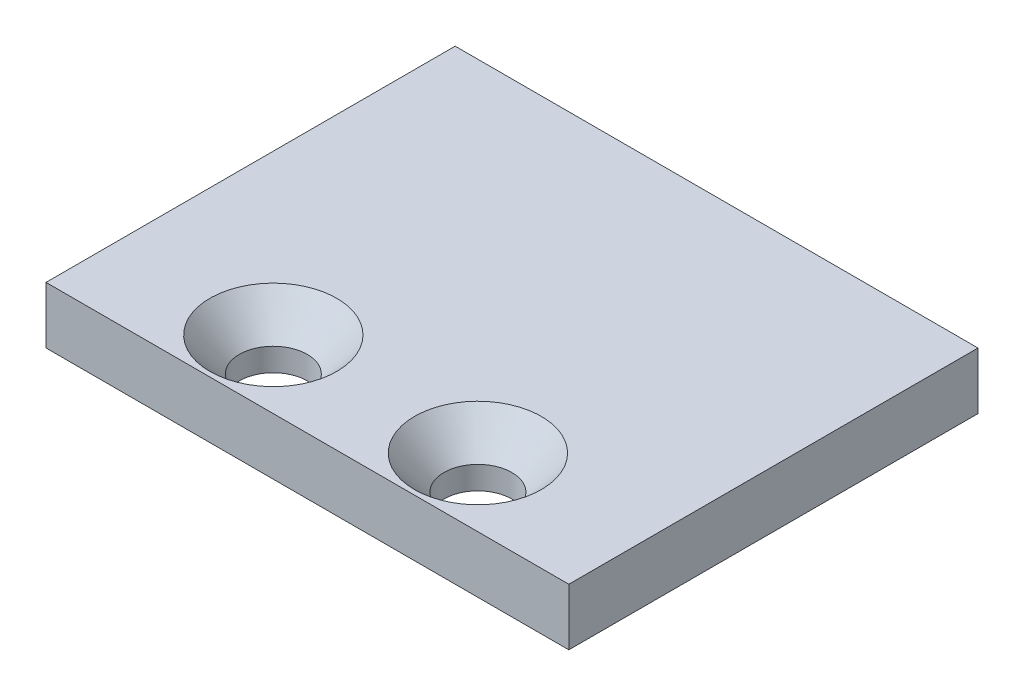
SolidWorks part; units mm, degrees
ref_plane "Front Plane" through (0, 0, 0) normal (0, 0, 1) x (1, 0, 0)
ref_plane "Top Plane" through (0, 0, 0) normal (0, 1, 0) x (1, 0, 0)
ref_plane "Right Plane" through (0, 0, 0) normal (1, 0, 0) x (0, 0, -1)
sketch "Sketch1" plane through (0, 0, 0) normal (0, 1, 0) x (1, 0, 0)
  line L1 (-14.605, -11.43) -> (14.605, -11.43)
  line L2 (-14.605, -11.43) -> (-14.605, 11.43)
  line L3 (-14.605, 11.43) -> (14.605, 11.43)
  line L4 (14.605, -11.43) -> (14.605, 11.43)
  line L5 (-14.605, -11.43) -> (14.605, 11.43) construction
  line L6 (-14.605, 11.43) -> (14.605, -11.43) construction
  point P0 (0, 0)
  dimension "D1" = 29.21
  dimension "D2" = 22.86
extrude "Boss-Extrude1" add sketch "Sketch1" along normal blind 3.175
sketch "Sketch2" plane through (0, 3.175, 0) normal (0, 1, 0) x (1, 0, 0)
  line L0 (-5.715, -7.62) -> (5.715, -7.62) construction
  line L1 (0, -1.7463) -> (0, 1.7463) construction
  line L2 (-14.605, -11.43) -> (14.605, -11.43) construction
  point P0 (-5.715, -7.62)
  point P1 (5.715, -7.62)
  point P2 (0, -7.62)
  dimension "D1" = 3.81
  dimension "D2" = 5.715
hole_wizard "CSK for #6 Flat Head Machine Screw1" positions "Sketch3" profile "Sketch5" countersink size "#6" standard "ANSI Inch" end condition through all
sketch "Sketch3" plane through (0, 3.175, 0) normal (0, 1, 0) x (1, 0, 0)
  point P0 (-5.715, -7.62)
  point P3 (5.715, -7.62)
sketch "Sketch5" plane through (-5.715, 3.175, 7.62) normal (1, 0, 0) x (0, 0, 1)
  line L0 (0, 0) -> (0, 3.175)
  line L1 (0, 3.175) -> (1.8986, 3.175)
  line L2 (1.8986, 3.175) -> (1.8986, 1.892)
  line L3 (1.8986, 1.892) -> (3.5433, 0)
  line L5 (3.5433, 0) -> (0, 0)
  line L6 (-1.8986, 1.892) -> (-3.5433, 0) construction
  line L11 (0, -6.35) -> (0, 107.95) construction
  dimension "Thru Hole Dia." = 3.7973
  dimension "Thru Hole Depth" = 3.175
  dimension "Near C'Sink Dia." = 7.0866
  dimension "Near C'Sink Angle" = 82
